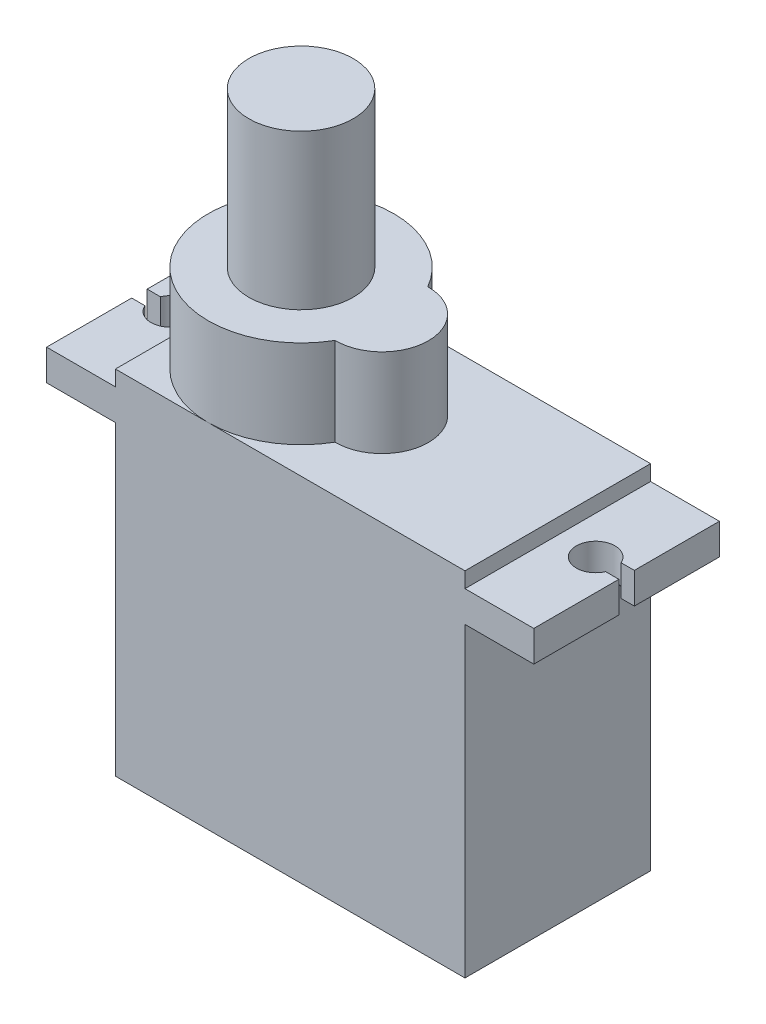
SolidWorks part; units mm, degrees
ref_plane "Piano frontale" through (0, 0, 0) normal (0, 0, 1) x (1, 0, 0)
ref_plane "Piano superiore" through (0, 0, 0) normal (0, 1, 0) x (1, 0, 0)
ref_plane "Piano destro" through (0, 0, 0) normal (1, 0, 0) x (0, 0, -1)
sketch "Schizzo1" plane through (0, 0, 0) normal (0, 1, 0) x (1, 0, 0)
  line L1 (0, 0) -> (22.6, 0)
  line L2 (0, 0) -> (0, 12)
  line L3 (0, 12) -> (22.6, 12)
  line L4 (22.6, 0) -> (22.6, 12)
  dimension "D1" = 22.6
  dimension "D2" = 12
extrude "Estrusione-Estrusione1" add sketch "Schizzo1" along normal blind 19.8
sketch "Schizzo3" plane through (0, 19.8, 0) normal (0, 1, 0) x (1, 0, 0)
  line L0 (-4.45, 0) -> (27.05, 0)
  line L1 (27.05, 0) -> (27.05, 12)
  line L2 (27.05, 12) -> (-4.45, 12)
  line L3 (-4.45, 12) -> (-4.45, 0)
  line L4 (0, 12) -> (0, 0) construction
  line L5 (22.6, 0) -> (22.6, 12) construction
  dimension "D1" = 4.45
  dimension "D2" = 4.45
  dimension "D3" = 12
extrude "Estrusione-Estrusione2" add sketch "Schizzo3" along normal blind 2 contours L3 L0 L1 L2
sketch "Schizzo4" plane through (0, 21.8, 0) normal (0, 1, 0) x (1, 0, 0)
  line L0 (27.05, 12) -> (-4.45, 12) construction
  line L1 (0, 0) -> (22.6, 0)
  line L2 (0, 0) -> (0, 12)
  line L3 (0, 12) -> (22.6, 12)
  line L4 (22.6, 0) -> (22.6, 12)
  line L6 (0, 12) -> (0, 0) construction
  dimension "D1" = 22.6
extrude "Estrusione-Estrusione3" add sketch "Schizzo4" along normal blind 1
sketch "Schizzo5" plane through (0, 22.8, 0) normal (0, 1, 0) x (1, 0, 0)
  line L0 (22.6, 12) -> (0, 12) construction
  line L1 (0, 12) -> (0, 0) construction
  circle A0 centre (6, 6) radius 6
  circle A1 centre (11.2364, 6) radius 3
  dimension "D1" = 6
  dimension "D2" = 6
  dimension "D4" = 12
  dimension "D3" = 5.2364
  dimension "D5" = 6
  dimension "D6" = 6
extrude "Estrusione-Estrusione4" add sketch "Schizzo5" along normal blind 5.7 contours A1 A0 | A0 A1 | A0 A1
sketch "Schizzo6" plane through (0, 28.5, 0) normal (0, 1, 0) x (1, 0, 0)
  circle A0 centre (6, 6) radius 3.375
  dimension "D1" = 6.75
extrude "Estrusione-Estrusione5" add sketch "Schizzo6" along normal blind 10
sketch "Schizzo7" plane through (0, 21.8, 0) normal (0, 1, 0) x (1, 0, 0)
  line L0 (27.05, 6) -> (-4.45, 6)
  line L1 (27.05, 0) -> (27.05, 12) construction
  line L2 (-4.45, 12) -> (-4.45, 0) construction
  line L4 (-4.45, 5.5) -> (-4.45, 6.5)
  line L5 (27.05, 5.5) -> (27.05, 6.5)
  line L6 (-4.45, 6.5) -> (-2.4491, 6.5)
  line L7 (-2.4491, 6.5) -> (-2.4491, 5.5)
  line L8 (-2.4491, 5.5) -> (-4.45, 5.5)
  line L9 (27.05, 6.5) -> (25.0476, 6.5)
  line L10 (25.0476, 6.5) -> (25.0476, 5.5)
  line L11 (25.0476, 5.5) -> (27.05, 5.5)
  circle A3 centre (-2.45, 6) radius 1.25
  circle A4 centre (25.05, 6) radius 1.25
  point P10 (-4.45, 6)
  point P12 (27.05, 6)
  line M3 (27.05, 0) -> (27.05, 12)
  dimension "D1" = 1
  dimension "D2" = 1
  dimension "D3" = 2.5
  dimension "D4" = 2.5
  dimension "D5" = 2
  dimension "D6" = 2
extrude "Taglio-Estrusione2" cut sketch "Schizzo7" against normal up to next contours A3 L0 L4 L8 | A3 L6 L4 L0 | L0 A3 L8 L7 | L0 A3 L6 L7 | L8 A3 L0 L7 | L6 A3 L0 L7 | L11 A4 L0 L10 | L0 A4 L11 L10 | L9 A4 L0 L10 | L0 A4 L9 L10 | A4 L0 L9 M3 | A4 L11 L0 M3
